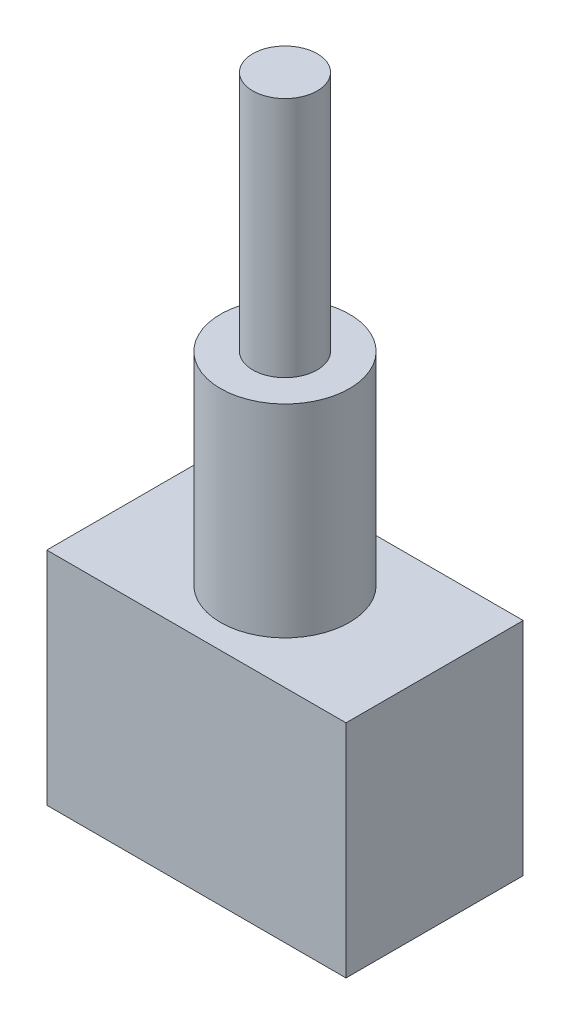
SolidWorks part; units mm, degrees
ref_plane "Front" through (0, 0, 0) normal (0, 0, 1) x (1, 0, 0)
ref_plane "Top" through (0, 0, 0) normal (0, 1, 0) x (1, 0, 0)
ref_plane "Right" through (0, 0, 0) normal (1, 0, 0) x (0, 0, -1)
sketch "Esboço2" plane through (0, 0, 0) normal (0, 0, 1) x (1, 0, 0)
  line L0 (0, 9.6) -> (13, 9.6)
  line L1 (13, 9.6) -> (13, 0)
  line L2 (13, 0) -> (0, 0)
  line L3 (0, 0) -> (0, 9.6)
  dimension "D1" = 13
  dimension "D2" = 9.6
extrude "Ressalto-extrusão1" add sketch "Esboço2" along normal blind 7.7
sketch "Esboço3" plane through (0, 9.6, 0) normal (0, 1, 0) x (1, 0, 0)
  line L0 (13, -7.7) -> (0, -7.7) construction
  circle A0 centre (6.5, -3.85) radius 2.8
  point P2 (6.7675, -4.1026)
  dimension "D1" = 5.6
  dimension "D2" = 3.85
  dimension "D3" = 6.5
extrude "Ressalto-extrusão2" add sketch "Esboço3" along normal blind 8.8
sketch "Esboço5" plane through (0, 18.4, 0) normal (0, 1, 0) x (1, 0, 0)
  line L0 (0, -7.7) -> (0, 0) construction
  line L1 (13, 0) -> (0, 0) construction
  circle A0 centre (6.5, -3.85) radius 1.4
  dimension "D1" = 2.8
  dimension "D2" = 6.5
  dimension "D3" = 3.85
extrude "Ressalto-extrusão3" add sketch "Esboço5" along normal blind 10.5
